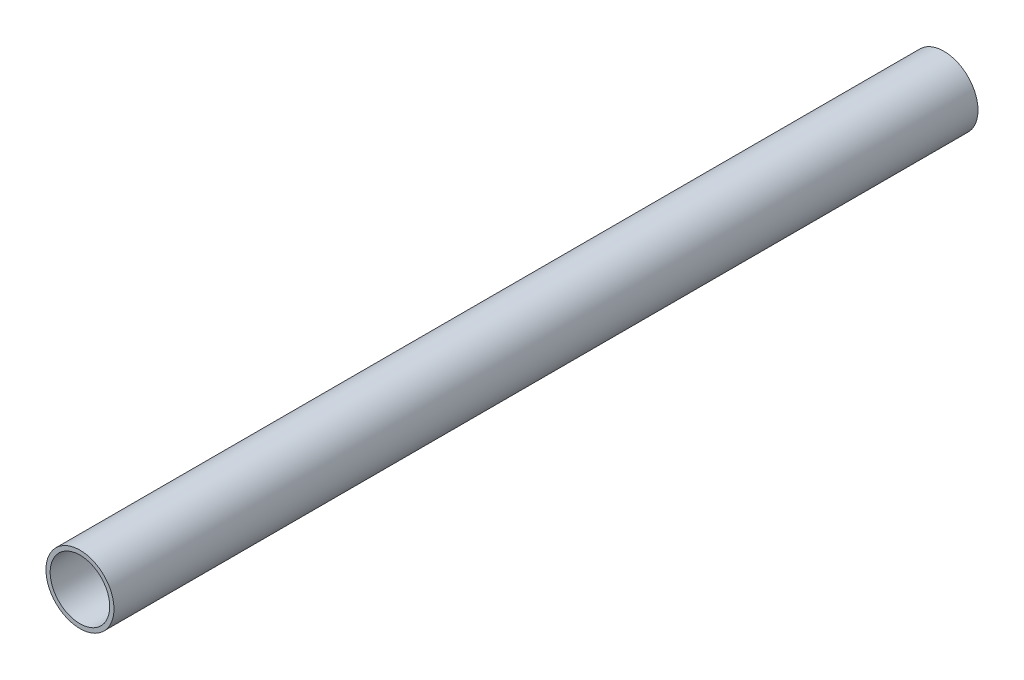
SolidWorks part; units mm, degrees
ref_plane "Front Plane" through (0, 0, 0) normal (0, 0, 1) x (1, 0, 0)
ref_plane "Top Plane" through (0, 0, 0) normal (0, 1, 0) x (1, 0, 0)
ref_plane "Right Plane" through (0, 0, 0) normal (1, 0, 0) x (0, 0, -1)
sketch "Sketch1" plane through (0, 0, 0) normal (0, 0, 1) x (1, 0, 0)
  circle A0 centre (0, 0) radius 7
  circle A1 centre (0, 0) radius 8
  dimension "D2" = 16
  dimension "D1" = 1
extrude "Boss-Extrude1" add sketch "Sketch1" along normal mid plane 203.2
